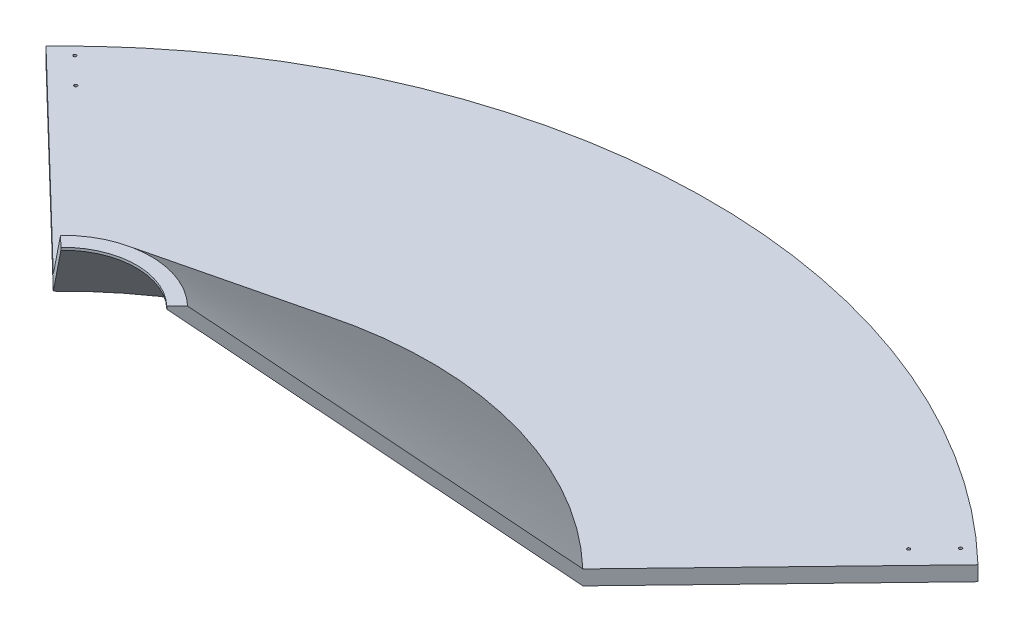
SolidWorks part; units mm, degrees
ref_plane "前视基准面" through (0, 0, 0) normal (0, 0, 1) x (1, 0, 0)
ref_plane "上视基准面" through (0, 0, 0) normal (0, 1, 0) x (1, 0, 0)
ref_plane "右视基准面" through (0, 0, 0) normal (1, 0, 0) x (0, 0, -1)
sketch "草图2" plane through (0, 0, 0) normal (0, 0, 1) x (1, 0, 0)
  line L0 (-422.3499, 6.0625) -> (-42.3499, 6.0625)
  line L1 (-42.3499, 6.0625) -> (337.6501, 320.5625)
  line L2 (337.6501, 320.5625) -> (357.6501, 320.5625)
  line L3 (357.6501, 320.5625) -> (357.6501, 317.1152)
  line L4 (357.6501, 317.1152) -> (-42.3499, -13.9375)
  line L5 (-42.3499, -13.9375) -> (-422.3499, -13.9375)
  line L6 (-422.3499, -13.9375) -> (-422.3499, 6.0625)
  line L7 (457.6501, 481.3151) -> (457.6501, -161.7992) construction
  dimension "D1" = 880
  dimension "D2" = 500
  dimension "D3" = 120
  dimension "D4" = 100
  dimension "D5" = 20
  dimension "D6" = 334.5
revolve "旋转1" add sketch "草图2" angle 360 about L7
sketch "草图3" plane through (0, 320.5625, 0) normal (0, 1, 0) x (1, 0, 0)
  line L0 (457.6501, 0) -> (1205.9506, 776.3418)
  line L1 (1205.9506, 776.3418) -> (29.2269, 1910.5625)
  line L2 (29.2269, 1910.5625) -> (-719.0736, 1134.2206)
  line L3 (-719.0736, 1134.2206) -> (457.6501, 0)
extrude "切除-拉伸1" cut sketch "草图3" against normal through all both and the other way through all flip side to cut contours L3 L0 L1 L2
sketch "草图7" plane through (0, -13.9375, 0) normal (0, -1, 0) x (1, 0, 0)
  line L0 (385.6511, -69.3984) -> (457.6501, 0) construction
  line L1 (457.6501, 0) -> (527.0485, -71.999) construction
  line L2 (1068.3562, -633.5914) -> (804.6422, -359.9951)
  line L3 (97.655, -346.9921) -> (-175.9413, -610.7061)
  line L4 (1068.3562, -633.5914) -> (804.6422, -359.9951) construction
  line L5 (97.655, -346.9921) -> (-175.9413, -610.7061) construction
  line L6 (804.6422, -359.9951) -> (527.0485, -71.999)
  line L7 (385.6511, -69.3984) -> (97.655, -346.9921)
  line L8 (804.6422, -359.9951) -> (527.0485, -71.999) construction
  line L9 (385.6511, -69.3984) -> (97.655, -346.9921) construction
  line L10 (406.7391, -49.0721) -> (506.7222, -50.911) construction
  line L11 (506.7222, -50.911) -> (508.5611, 49.0721) construction
  line L12 (508.5611, 49.0721) -> (408.578, 50.911) construction
  line L14 (406.7391, -49.0721) -> (408.578, 50.911) construction
  line L15 (506.7222, -50.911) -> (408.578, 50.911) construction
  line L16 (406.7391, -49.0721) -> (395.7039, -649.0721) construction
  line L17 (506.7222, -50.911) -> (495.687, -650.911) construction
  line L19 (395.3728, -667.0721) -> (405.3728, -667.0721)
  line L20 (405.3728, -667.0721) -> (406.0349, -631.0721)
  line L21 (406.0349, -631.0721) -> (396.0349, -631.0721)
  line L23 (395.7039, -649.0721) -> (395.3728, -667.0721)
  line L24 (396.0349, -631.0721) -> (395.7039, -649.0721)
  line L30 (495.687, -650.911) -> (496.018, -632.911)
  line L31 (496.018, -632.911) -> (486.018, -632.911)
  line L32 (486.018, -632.911) -> (486.018, -668.908)
  line L33 (486.018, -668.908) -> (495.356, -668.908)
  line L34 (495.356, -668.908) -> (495.687, -650.911)
  arc A2 (-175.9413, -610.7061) -> (1068.3562, -633.5914) centre (457.6501, 0) ccw
  arc A3 (97.655, -346.9921) -> (804.6422, -359.9951) centre (457.6501, 0) ccw
  arc A4 (-175.9413, -610.7061) -> (1068.3562, -633.5914) centre (457.6501, 0) ccw construction
  arc A5 (97.655, -346.9921) -> (804.6422, -359.9951) centre (457.6501, 0) ccw construction
  arc A6 (97.655, -346.9921) -> (804.6422, -359.9951) centre (457.6501, 0) ccw
  arc A7 (385.6511, -69.3984) -> (527.0485, -71.999) centre (457.6501, 0) ccw
  arc A8 (97.655, -346.9921) -> (804.6422, -359.9951) centre (457.6501, 0) ccw construction
  arc A9 (385.6511, -69.3984) -> (527.0485, -71.999) centre (457.6501, 0) ccw construction
  dimension "D2" = 0
  dimension "D3" = 100
  dimension "D4" = 600
  dimension "D5" = 18
  dimension "D6" = 10
  dimension "D7" = 36
  dimension "D8" = 10
  dimension "D9" = 18
  dimension "D10" = 18
  dimension "D11" = 10
  dimension "D1" = 0
extrude "切除-拉伸5" cut sketch "草图7" against normal blind 10
sketch "草图8" plane through (0, 6.0625, 0) normal (0, 1, 0) x (1, 0, 0)
  line L0 (-175.9413, 610.7061) -> (97.655, 346.9921) construction
  line L1 (540.9282, 86.3988) -> (804.6422, 359.9951) construction
  circle A0 centre (-109.1717, 584.5433) radius 2.5
  circle A1 centre (-145.1712, 619.2425) radius 2.5
  dimension "D1" = 5
  dimension "D2" = 27.5
  dimension "D3" = 813.77
  dimension "D4" = 2
hole_wizard "M5 螺纹孔1" positions "3D草图1" profile "草图9" tap size "M5" standard "GB" end condition up to next
sketch3d "3D草图1"
  point P0 (-145.1712, 6.0625, -619.2425)
  point P3 (-109.1717, 6.0625, -584.5433)
sketch "草图9" plane through (-145.1712, 6.0625, -619.2425) normal (1, 0, 0) x (0, 0, 1)
  line L0 (0, 0) -> (0, 20)
  line L1 (0, 20) -> (2.1, 20)
  line L2 (2.1, 20) -> (2.1, 0)
  line L5 (2.1, 0) -> (0, 0)
  line L11 (0, -6.35) -> (0, 107.95) construction
  dimension "通孔螺纹孔钻头直径" = 4.2
  dimension "通孔螺纹孔钻头深度" = 20
ref_plane "基准面1" through (457.4954, 0, -8.4143) normal (-0.9998, 0, 0.0184) x (0.0184, 0, 0.9998)
mirror "镜向1" about plane through (457.4954, 0, -8.4143) normal (-0.9998, 0, 0.0184) of "M5 螺纹孔1"
